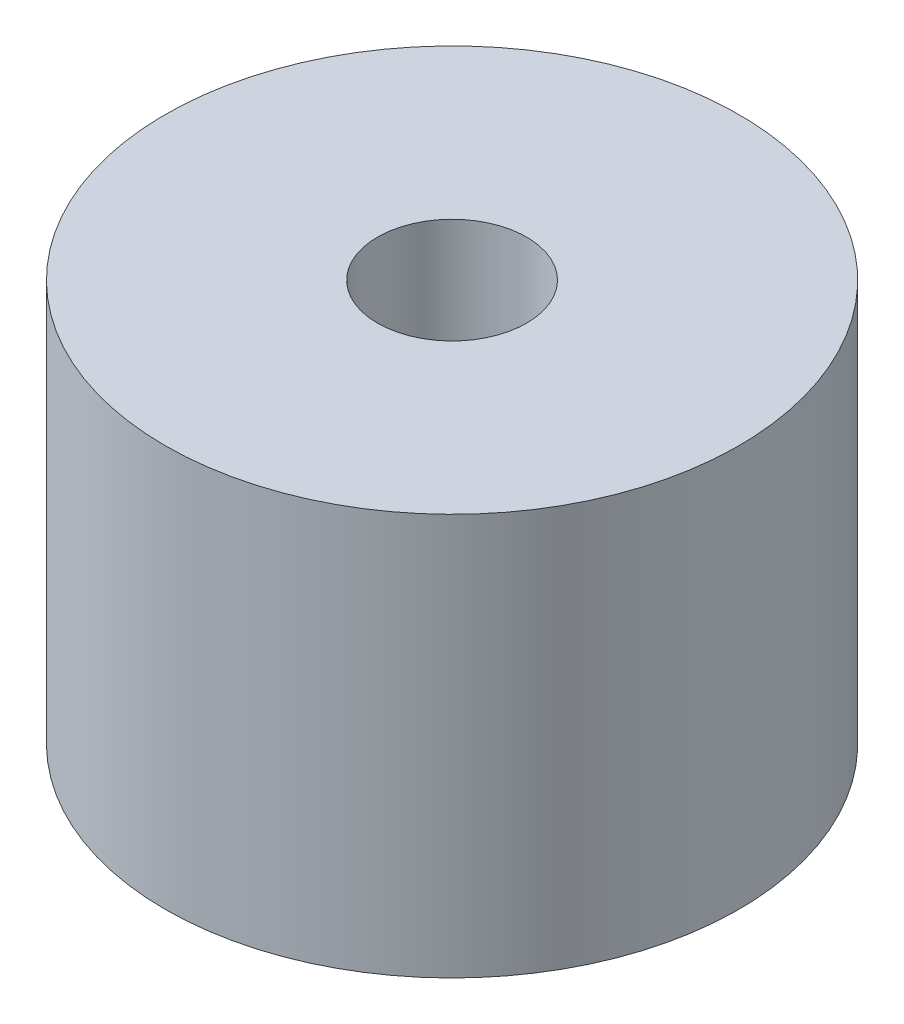
SolidWorks part; units mm, degrees
ref_plane "Ön Düzlem" through (0, 0, 0) normal (0, 0, 1) x (1, 0, 0)
ref_plane "Üst Düzlem" through (0, 0, 0) normal (0, 1, 0) x (1, 0, 0)
ref_plane "Sağ Düzlem" through (0, 0, 0) normal (1, 0, 0) x (0, 0, -1)
sketch "Çizim1" plane through (0, 0, 0) normal (0, 1, 0) x (1, 0, 0)
  circle A0 centre (0, 0) radius 25
  dimension "D1" = 50
extrude "Yükseklik-Ekstrüzyon1" add sketch "Çizim1" along normal blind 35
sketch "Çizim2" plane through (0, 35, 0) normal (0, 1, 0) x (1, 0, 0)
  circle A0 centre (0, 0) radius 6.5
  dimension "D1" = 13
extrude "Kes-Ekstrüzyon1" cut sketch "Çizim2" against normal blind 30
sketch "Çizim3" plane through (0, 5, 0) normal (0, 1, 0) x (1, 0, 0)
  circle A0 centre (0, 0) radius 2.5
  dimension "D1" = 5
extrude "Kes-Ekstrüzyon2" cut sketch "Çizim3" against normal blind 3
sketch "Çizim4" plane through (0, 2, 0) normal (0, 1, 0) x (1, 0, 0)
  circle A0 centre (0, 0) radius 1.5
  dimension "D1" = 3
extrude "Kes-Ekstrüzyon3" cut sketch "Çizim4" against normal through all
